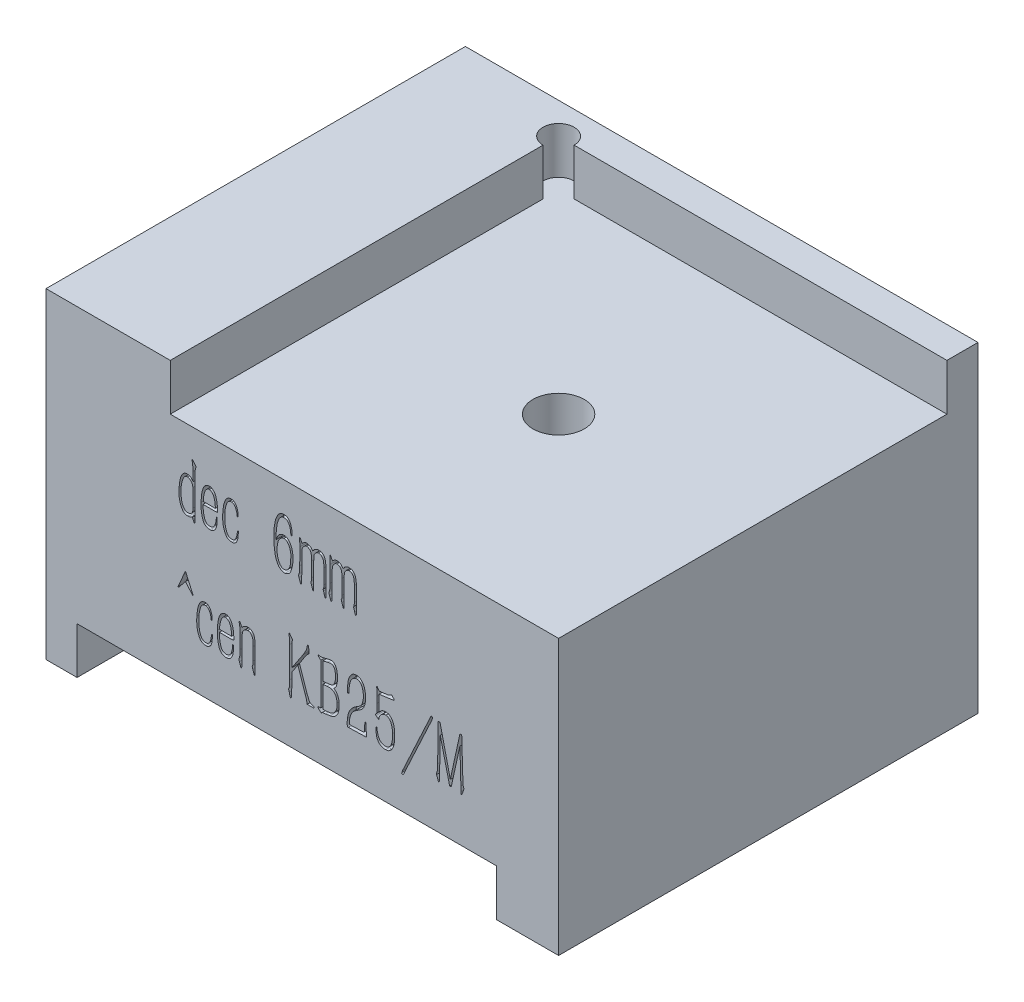
SolidWorks part; units mm, degrees
material "6061 合金"
ref_plane "前视基准面" through (0, 0, 0) normal (0, 0, 1) x (1, 0, 0)
ref_plane "上视基准面" through (0, 0, 0) normal (0, 1, 0) x (1, 0, 0)
ref_plane "右视基准面" through (0, 0, 0) normal (1, 0, 0) x (0, 0, -1)
sketch "草图1" plane through (0, 0, 0) normal (0, 1, 0) x (1, 0, 0)
  line L1 (-14.5, 14.5) -> (14.5, 14.5)
  line L2 (-14.5, 14.5) -> (-14.5, -14.5)
  line L3 (-14.5, -14.5) -> (14.5, -14.5)
  line L4 (14.5, 14.5) -> (14.5, -14.5)
  line L5 (-14.5, 14.5) -> (14.5, -14.5) construction
  line L6 (-14.5, -14.5) -> (14.5, 14.5) construction
  point P0 (0, 0)
  dimension "D1" = 29
  dimension "D2" = 29
extrude "凸台-拉伸1" add sketch "草图1" along normal blind 5
sketch "草图2" plane through (0, 5, 0) normal (0, -1, 0) x (1, 0, 0)
  line L1 (-12.5, 12.5) -> (12.5, 12.5)
  line L2 (-12.5, 12.5) -> (-12.5, -12.5)
  line L3 (-12.5, -12.5) -> (12.5, -12.5)
  line L4 (12.5, 12.5) -> (12.5, -12.5)
  line L5 (-12.5, 12.5) -> (12.5, -12.5) construction
  line L6 (-12.5, -12.5) -> (12.5, 12.5) construction
  point P0 (0, 0)
  dimension "D1" = 25
  dimension "D2" = 25
extrude "切除-拉伸1" cut sketch "草图2" along normal blind 3
sketch "草图3" plane through (0, 0, 0) normal (0, -1, 0) x (-1, 0, 0)
  line L1 (-14.5, -14.5) -> (20.5, -14.5)
  line L2 (-14.5, -14.5) -> (-14.5, 14.5)
  line L3 (-14.5, 14.5) -> (20.5, 14.5)
  line L4 (20.5, -14.5) -> (20.5, 14.5)
  dimension "D1" = 29
  dimension "D2" = 35
extrude "拉到底部滑块" add sketch "草图3" along normal up to surface (12.6823 mm away)
sketch "草图4" plane through (0, -12.6823, 0) normal (0, -1, 0) x (1, 0, 0)
  line L0 (0, 0) -> (-6, 0) construction
  line L1 (16.5, 0) -> (-16.5, 0) construction
  line L2 (-20.5, 14.5) -> (8.5, 14.5)
  line L3 (-18.5, 12.5) -> (6.5, 12.5)
  line L4 (-18.5, 12.5) -> (-18.5, -12.5)
  line L5 (-18.5, -12.5) -> (6.5, -12.5)
  line L6 (6.5, 12.5) -> (6.5, -12.5)
  line L7 (-18.5, 12.5) -> (6.5, -12.5) construction
  line L8 (-18.5, -12.5) -> (6.5, 12.5) construction
  line L9 (8.5, 14.5) -> (8.5, -14.5)
  line L10 (-20.5, -14.5) -> (8.5, -14.5)
  line L11 (-20.5, 14.5) -> (-20.5, -14.5)
  dimension "D1" = 6
  dimension "D2" = 25
  dimension "D3" = 25
  dimension "D4" = 2
extrude "凸台-拉伸3" add sketch "草图4" along normal blind 3
sketch "草图5" plane through (0, 2, 0) normal (0, 1, 0) x (1, 0, 0)
  circle A0 centre (0, 0) radius 2.1526
hole_wizard "M4 螺纹孔1" positions "3D草图1" profile "草图6" tap size "M4" standard "GB"
sketch3d "3D草图1"
  point P0 (0, 2, 0)
sketch "草图6" plane through (0, 2, 0) normal (1, 0, 0) x (0, 0, 1)
  line L0 (0, 0) -> (0, 11.0914)
  line L1 (0, 11.0914) -> (1.65, 10.1)
  line L2 (1.65, 10.1) -> (1.65, 0)
  line L5 (1.65, 0) -> (0, 0)
  line L10 (0, 11.0914) -> (-1.65, 10.1) construction
  line L11 (0, -6.35) -> (0, 107.95) construction
  dimension "螺纹孔钻头直径" = 3.3
  dimension "螺纹孔钻头深度" = 10.1
  dimension "导头角度" = 118
cosmetic thread "孔螺蚊线1" parameters "D1"=8, "D2"=4
sketch "草图7" plane through (0, -12.6823, 0) normal (0, -1, 0) x (1, 0, 0)
  line L0 (-6, 12.5) -> (-6, -12.5) construction
  line L1 (6.5, 12.5) -> (-18.5, 12.5) construction
  line L2 (-18.5, -12.5) -> (6.5, -12.5) construction
  circle A0 centre (-6, 0) radius 1.2473
hole_wizard "M4 螺纹孔2" positions "3D草图2" profile "草图8" tap size "M4" standard "GB"
sketch3d "3D草图2"
  point P0 (-6, -12.6823, 0)
sketch "草图8" plane through (-6, -12.6823, 0) normal (1, 0, 0) x (0, 0, -1)
  line L0 (0, 0) -> (0, 11.0914)
  line L1 (0, 11.0914) -> (1.65, 10.1)
  line L2 (1.65, 10.1) -> (1.65, 0)
  line L5 (1.65, 0) -> (0, 0)
  line L10 (0, 11.0914) -> (-1.65, 10.1) construction
  line L11 (0, -6.35) -> (0, 107.95) construction
  dimension "螺纹孔钻头直径" = 3.3
  dimension "螺纹孔钻头深度" = 10.1
  dimension "导头角度" = 118
cosmetic thread "孔螺蚊线2" parameters "D1"=8, "D2"=4
sketch "草图9" plane through (0, 5, 0) normal (0, 1, 0) x (1, 0, 0)
  circle A0 centre (-12.5, 12.5) radius 1
extrude "切除-拉伸2" cut sketch "草图9" against normal up to surface (3 mm away) up to face at (0, 2, 1.65)
sketch "草图10" plane through (0, -15.6823, 0) normal (0, -1, 0) x (1, 0, 0)
  circle A0 centre (-18.5, -12.5) radius 1
extrude "切除-拉伸3" cut sketch "草图10" against normal up to surface (3 mm away) up to face at (-6, -12.6823, -1.65)
sketch "草图11" plane through (-14.5, 0, 0) normal (-1, 0, 0) x (0, 0, 1)
  line L4 (-14.5, 0) -> (14.5, 0)
  line L5 (14.5, 0) -> (14.5, 5)
  line L6 (14.5, 5) -> (-14.5, 5)
  line L7 (-14.5, 5) -> (-14.5, 0)
  line L8 (-14.5, 0) -> (14.5, 0)
  line L9 (14.5, 0) -> (14.5, 5)
  line L10 (14.5, 5) -> (-14.5, 5)
  line L11 (-14.5, 5) -> (-14.5, 0)
  dimension "D1" = 0
extrude "凸台-拉伸4" add sketch "草图11" along normal up to surface (6 mm away) up to face at (-20.5, -7.8412, 0)
sketch "草图12" plane through (8.5, 0, 0) normal (1, 0, 0) x (0, 0, -1)
  line L4 (14.5, -12.6823) -> (-14.5, -12.6823)
  line L5 (-14.5, -12.6823) -> (-14.5, -15.6823)
  line L6 (-14.5, -15.6823) -> (14.5, -15.6823)
  line L7 (14.5, -15.6823) -> (14.5, -12.6823)
  line L8 (14.5, -12.6823) -> (-14.5, -12.6823)
  line L9 (-14.5, -12.6823) -> (-14.5, -15.6823)
  line L10 (-14.5, -15.6823) -> (14.5, -15.6823)
  line L11 (14.5, -15.6823) -> (14.5, -12.6823)
  dimension "D1" = 0
extrude "凸台-拉伸5" add sketch "草图12" along normal up to surface (6 mm away) up to face at (14.5, -3.8412, 0)
sketch "草图13" plane through (6.5, 0, 0) normal (-1, 0, 0) x (0, 0, 1)
  line L4 (12.5, -12.6823) -> (-12.5, -12.6823)
  line L5 (-12.5, -12.6823) -> (-12.5, -15.6823)
  line L6 (-12.5, -15.6823) -> (12.5, -15.6823)
  line L7 (12.5, -15.6823) -> (12.5, -12.6823)
  line L8 (12.5, -12.6823) -> (-12.5, -12.6823)
  line L9 (-12.5, -12.6823) -> (-12.5, -15.6823)
  line L10 (-12.5, -15.6823) -> (12.5, -15.6823)
  line L11 (12.5, -15.6823) -> (12.5, -12.6823)
  dimension "D1" = 0
extrude "切除-拉伸4" cut sketch "草图13" against normal blind 2
sketch "草图14" plane through (0, 0, 12.5) normal (0, 0, -1) x (-1, 0, 0)
  line L4 (18.5, -12.6823) -> (-8.5, -12.6823)
  line L5 (-8.5, -12.6823) -> (-8.5, -15.6823)
  line L6 (-8.5, -15.6823) -> (18.5, -15.6823)
  line L7 (18.5, -15.6823) -> (18.5, -12.6823)
  line L8 (18.5, -12.6823) -> (-8.5, -12.6823)
  line L9 (-8.5, -12.6823) -> (-8.5, -15.6823)
  line L10 (-8.5, -15.6823) -> (18.5, -15.6823)
  line L11 (18.5, -15.6823) -> (18.5, -12.6823)
  dimension "D1" = 0
extrude "切除-拉伸5" cut sketch "草图14" against normal through all
fillet "圆角1" radius 1 1 edges at (8.5, -14.1823, -12.5)
sketch "草图15" plane through (12.5, 0, 0) normal (-1, 0, 0) x (0, 0, 1)
  line L4 (12.5, 5) -> (-12.5, 5)
  line L5 (-12.5, 5) -> (-12.5, 2)
  line L6 (-12.5, 2) -> (12.5, 2)
  line L7 (12.5, 2) -> (12.5, 5)
  line L8 (12.5, 5) -> (-12.5, 5)
  line L9 (-12.5, 5) -> (-12.5, 2)
  line L10 (-12.5, 2) -> (12.5, 2)
  line L11 (12.5, 2) -> (12.5, 5)
  dimension "D1" = 0
sketch "草图16" plane through (0, 0, 12.5) normal (0, 0, -1) x (-1, 0, 0)
  line L4 (12.5, 5) -> (-14.5, 5)
  line L5 (-14.5, 5) -> (-14.5, 2)
  line L6 (-14.5, 2) -> (12.5, 2)
  line L7 (12.5, 2) -> (12.5, 5)
  line L8 (12.5, 5) -> (-14.5, 5)
  line L9 (-14.5, 5) -> (-14.5, 2)
  line L10 (-14.5, 2) -> (12.5, 2)
  line L11 (12.5, 2) -> (12.5, 5)
  dimension "D1" = 0
sketch "草图17" plane through (0, 5, 0) normal (0, 1, 0) x (1, 0, 0)
  line L0 (-20.5, -14.5) -> (14.5, -14.5) construction
  line L1 (14.5, -14.5) -> (14.5, 14.5) construction
  line L2 (-20.5, -14.5) -> (14.5, -14.5)
  line L3 (14.5, -14.5) -> (14.5, 14.5)
  line L4 (-20.5, -12.5) -> (12.5, -12.5)
  line L5 (12.5, -12.5) -> (12.5, 14.5)
  line L6 (12.5, 14.5) -> (14.5, 14.5)
  line L7 (-20.5, -12.5) -> (-20.5, -14.5)
  dimension "D1" = 2
extrude "切除-拉伸8" cut sketch "草图17" against normal through all
sketch "草图19" plane through (0, 0, 12.5) normal (0, 0, 1) x (1, 0, 0)
  text T0 "dec 6mm\r\n^cen KB25/M "
extrude "切除-拉伸9" cut sketch "草图19" against normal blind 0.5
